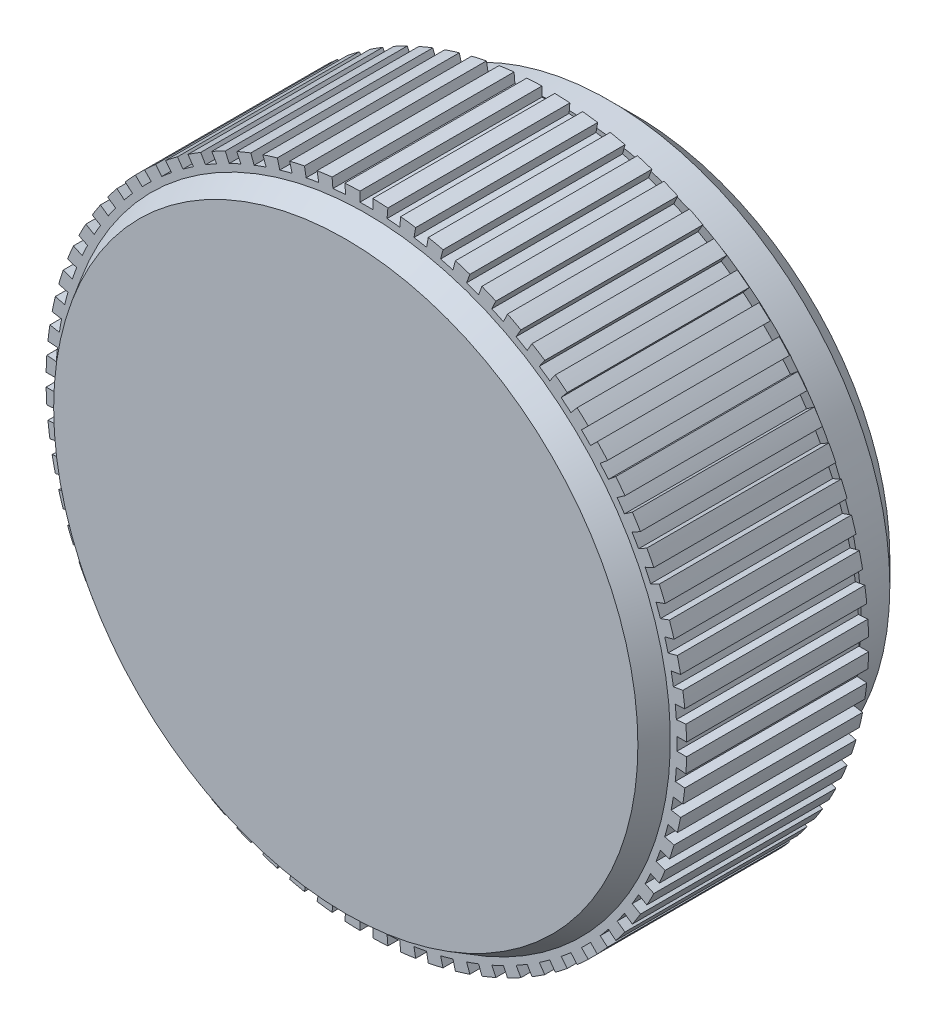
SolidWorks part; units mm, degrees
ref_plane "Front" through (0, 0, 0) normal (0, 0, 1) x (1, 0, 0)
ref_plane "Top" through (0, 0, 0) normal (0, 1, 0) x (1, 0, 0)
ref_plane "Right" through (0, 0, 0) normal (1, 0, 0) x (0, 0, -1)
sketch "Sketch20" plane through (0, 0, 0) normal (1, 0, 0) x (0, 0, -1)
  line L2 (0, 5) -> (0, -5) construction
  line L3 (-4.5, 5) -> (-4.5, -5) construction
  point P11 (0, 0)
  dimension "Head Diameter" = 10
  dimension "Head Height" = 4.5
sketch "Sketch1" plane through (0, 0, 0) normal (0, 0, 1) x (1, 0, 0)
  circle A0 centre (0, 0) radius 3.175
  dimension "dia" = 6.35
extrude "Extrude1" add sketch "Sketch1" along normal blind 3.175
sketch "Sketch21" plane through (0, 0, 0) normal (0, 0, 1) x (1, 0, 0)
  line L0 (-5, 0) -> (5, 0) construction
  line L1 (-5, 1.5875) -> (5, 1.5875) construction
  line L2 (0, 0) -> (0, 1.5875) construction
  circle A0 centre (0, 0) radius 5
  dimension "D1" = 1.5875
extrude "Boss-Extrude1" add sketch "Sketch21" along normal up to vertex (4.5 mm away) up to point (0, -5, 4.5)
sketch "Sketch34" plane through (0, 0, 0) normal (0, 0, -1) x (-1, 0, 0)
  circle A0 centre (0, 0) radius 4.375
  circle A1 centre (0, 0) radius 5
  circle A2 centre (0, 0) radius 5 construction
  dimension "D1" = 8.75
extrude "Cut-Extrude4" cut sketch "Sketch34" against normal blind 1.016
ref_plane "Plane1" through (0, 5, 0) normal (0, 1, 0) x (-1, 0, 0)
sketch "Sketch22" plane through (0, 5, 0) normal (0, 1, 0) x (-1, 0, 0)
  line L0 (0, 4.5) -> (0, 0) construction
  line L1 (-0.1, 4.5) -> (0.1, 4.5)
  line L3 (-0.1, 4.5) -> (-0.1, 0)
  line L4 (-0.1, 0) -> (0.1, 0)
  line L7 (0.1, 4.5) -> (0.1, 0)
  dimension "D1" = 0.2
extrude "Cut-Extrude1" cut sketch "Sketch22" against normal offset from surface (0.151 mm away) 0.15
pattern_circular "CirPattern1" count 72 over 360 about axis through (0, 0, 0) along (0, 0, 1) of "Cut-Extrude1"
sketch "Sketch29" plane through (0, 0, 0) normal (1, 0, 0) x (0, 0, -1)
  line L0 (-4.1786, 4.746) -> (-4.5, 4.5604)
  line L1 (-4.5, 4.5604) -> (-4.5, 5.254)
  line L2 (-4.1786, 4.746) -> (-4.1786, 5.254)
  line L3 (-4.5, 5.254) -> (-4.1786, 5.254)
  line L5 (0, 0) -> (-2.758, 0) construction
  line L6 (-4.5, 5) -> (-1.016, 5) construction
  line L7 (-2.758, 5) -> (-2.758, 0) construction
  line L8 (-1.016, 5.254) -> (-1.3374, 5.254)
  line L9 (-1.3374, 4.746) -> (-1.3374, 5.254)
  line L10 (-1.016, 4.5604) -> (-1.016, 5.254)
  line L11 (-1.3374, 4.746) -> (-1.016, 4.5604)
  line L26 (-1.016, 4.7317) -> (-1.016, 4.8028) construction
  dimension "D1" = 0.254
  dimension "D2" = 30
  dimension "D3" = 0.254
  dimension "D4" = 0.3214
revolve "Cut-Revolve1" cut sketch "Sketch29" angle 360 about L5
chamfer "Chamfer3" distance 0.381 angle 45 1 edges at (-4.375, 0, 0)
sketch "Sketch35" plane through (0, 0, 0) normal (0, 0, 1) x (1, 0, 0)
  circle A0 centre (0, 0) radius 2.75
  circle A1 centre (0, 0) radius 1.25
  dimension "D1" = 5.5
  dimension "D2" = 2.5
extrude "Cut-Extrude5" cut sketch "Sketch35" along normal offset from surface (1.5 mm away) 3 up to face at (-4.5604, 0, 4.5)
sketch "Sketch36" plane through (0, 0, 0) normal (0, 0, -1) x (-1, 0, 0)
  circle A1 centre (0, 0) radius 1.25
  circle A2 centre (0, 0) radius 1.25
  dimension "D1" = 0
extrude "Cut-Extrude6" cut sketch "Sketch36" against normal offset from surface (3.024 mm away) 1.524 up to face at (1.25, 0, 1.5)
equation "\"D4@Sketch29\" = \"Head Height@Sketch20\"/14"
equation "\"D1@Sketch34\" = \"D1@Sketch35\"+3.250"
